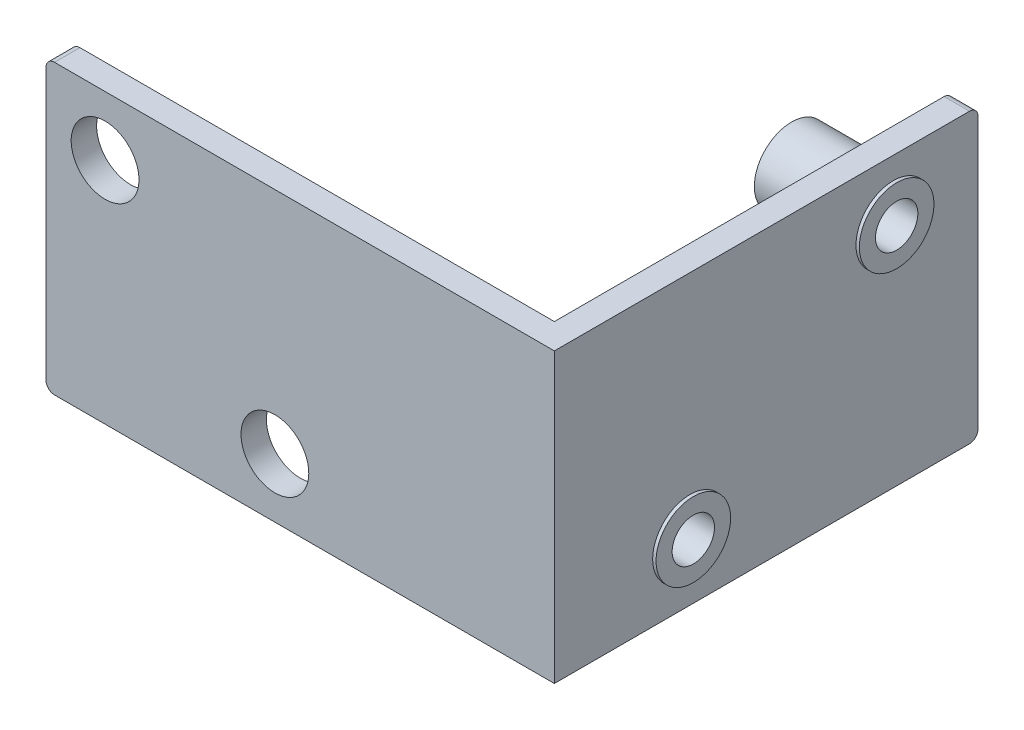
SolidWorks part; units mm, degrees
material "Aluminium"
ref_plane "Plan de face" through (0, 0, 0) normal (0, 0, 1) x (1, 0, 0)
ref_plane "Plan de dessus" through (0, 0, 0) normal (0, 1, 0) x (1, 0, 0)
ref_plane "Plan de droite" through (0, 0, 0) normal (1, 0, 0) x (0, 0, -1)
sketch "Esquisse1" plane through (0, 0, 0) normal (0, 0, 1) x (1, 0, 0)
  line L1 (-8.9489, -18.5667) -> (21.0511, -18.5667)
  line L2 (-8.9489, -18.5667) -> (-8.9489, -1.5667)
  line L3 (-8.9489, -1.5667) -> (21.0511, -1.5667)
  line L4 (21.0511, -18.5667) -> (21.0511, -1.5667)
  dimension "D1" = 30
extrude "Extrusion1" add sketch "Esquisse1" along normal blind 1.5
sketch "Esquisse2" plane through (0, 0, 1.5) normal (0, 0, 1) x (1, 0, 0)
  circle A0 centre (-5.4631, -5.0762) radius 2
  circle A1 centre (4.5584, -15.0701) radius 2
extrude "Enlèv. mat.-Extru.1" cut sketch "Esquisse2" against normal blind 2
sketch "Esquisse3" plane through (0, 0, 0) normal (0, 0, -1) x (-1, 0, 0)
  line L0 (8.9489, -18.5667) -> (-21.0511, -18.5667) construction
  line L1 (-21.0511, -1.5667) -> (-19.5511, -1.5667)
  line L2 (-21.0511, -1.5667) -> (-21.0511, -18.5667)
  line L3 (-21.0511, -18.5667) -> (-19.5511, -18.5667)
  line L4 (-19.5511, -1.5667) -> (-19.5511, -18.5667)
  dimension "D1" = 1.5
extrude "Extrusion2" add sketch "Esquisse3" along normal blind 23.5
sketch "Esquisse4" plane through (21.0511, 0, 0) normal (1, 0, 0) x (0, 0, -1)
  line L0 (-1.5, -10.0667) -> (22.2784, -10.0667) construction
  line L1 (-1.5, -18.5667) -> (-1.5, -1.5667) construction
  line L2 (11, -1.5667) -> (11, -17.0068) construction
  line L3 (-1.5, -1.5667) -> (23.5, -1.5667) construction
  line L4 (-3, -15.0667) -> (15.7036, -15.0667) construction
  line L6 (-3, -5.0667) -> (20.9635, -5.0667) construction
  circle A0 centre (6.5, -15.1074) radius 1.25
  circle A1 centre (18.5, -5.0667) radius 1.25
  dimension "D1" = 7.5
  dimension "D2" = 4.5
extrude "Enlèv. mat.-Extru.2" cut sketch "Esquisse4" against normal blind 2
sketch "Esquisse5" plane through (21.0511, 0, 0) normal (1, 0, 0) x (0, 0, -1)
  circle A0 centre (6.5, -15.1074) radius 1.25
  circle A1 centre (6.5, -15.1074) radius 2.2
  circle A2 centre (18.5, -5.0667) radius 1.25
  circle A3 centre (18.5, -5.0667) radius 2.2
extrude "Extrusion3" add sketch "Esquisse5" along normal blind 0.2 and the other way blind 6
fillet "Congé1" radius 0.5 4 edges at (20.3011, -18.5667, -23.5) (20.3011, -1.5667, -23.5) (-8.9489, -18.5667, 0.75) (-8.9489, -1.5667, 0.75)
